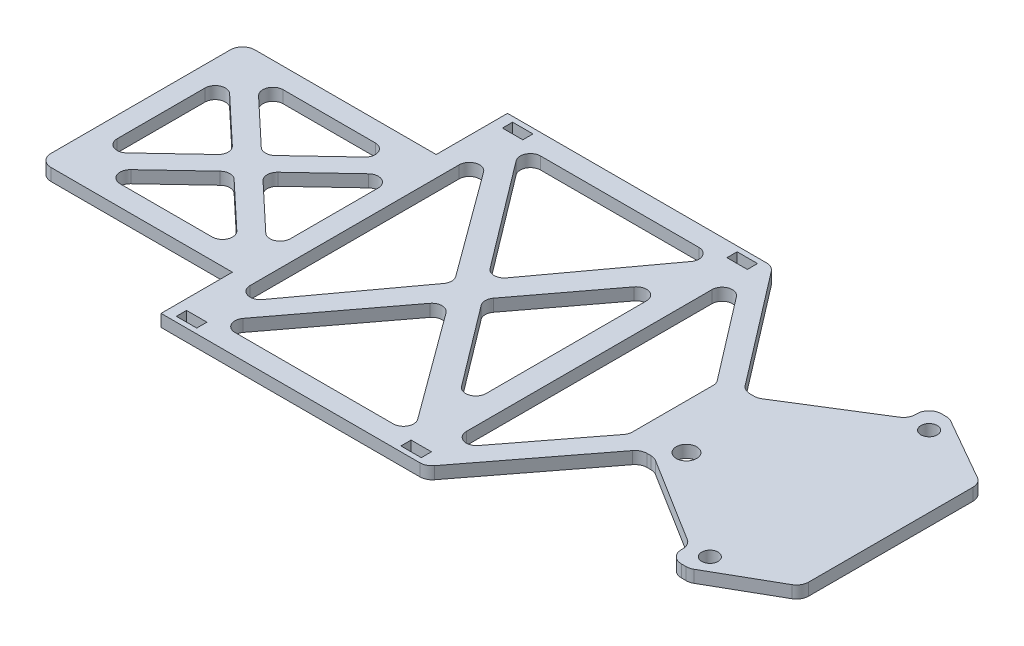
SolidWorks part; units mm, degrees
ref_plane "Front Plane" through (0, 0, 0) normal (0, 0, 1) x (1, 0, 0)
ref_plane "Top Plane" through (0, 0, 0) normal (0, 1, 0) x (1, 0, 0)
ref_plane "Right Plane" through (0, 0, 0) normal (1, 0, 0) x (0, 0, -1)
sketch "Sketch1" plane through (0, 0, 0) normal (0, 1, 0) x (1, 0, 0)
  line L0 (35, -25) -> (35, -35)
  line L1 (0, 0) -> (70, 0)
  line L2 (0, 0) -> (0, -25)
  line L3 (0, -25) -> (70, -25)
  line L4 (70, 0) -> (70, -25)
  line L5 (35, -35) -> (35, -85) construction
  line L6 (35, -85) -> (285, -85) construction
  line L7 (70, -170) -> (70, -145)
  line L8 (0, -145) -> (70, -145)
  line L9 (0, -170) -> (0, -145)
  line L10 (0, -170) -> (70, -170)
  line L11 (35, -145) -> (35, -135)
  line L12 (277.3319, -59.724) -> (274.2495, -59.724)
  line L13 (70, -170) -> (70, -145)
  line L14 (0, -170) -> (0, -145)
  line L15 (0, 0) -> (0, -25)
  line L16 (70, 0) -> (70, -25)
  line L17 (0, 0) -> (0, -25)
  line L18 (70, 0) -> (70, -25)
  line L19 (70, -170) -> (70, -145)
  line L20 (0, -170) -> (0, -145)
  line L21 (70, -170) -> (70, -145)
  line L22 (0, -170) -> (0, -145)
  line L23 (0, 0) -> (0, -25)
  line L24 (70, 0) -> (70, -25)
  line L25 (0, 0) -> (0, -25)
  line L26 (70, 0) -> (70, -25)
  line L27 (70, -170) -> (70, -145)
  line L28 (0, -170) -> (0, -145)
  line L29 (70, -170) -> (70, -145)
  line L30 (0, -170) -> (0, -145)
  line L31 (0, 0) -> (0, -25)
  line L32 (70, 0) -> (70, -25)
  line L33 (0, 0) -> (0, -25)
  line L34 (70, 0) -> (70, -25)
  line L35 (70, -170) -> (70, -145)
  line L36 (0, -170) -> (0, -145)
  line L37 (70, -170) -> (70, -145)
  line L38 (0, -170) -> (0, -145)
  line L39 (0, 0) -> (0, -25)
  line L40 (70, 0) -> (70, -25)
  line L41 (0, 0) -> (0, -25)
  line L42 (70, 0) -> (70, -25)
  line L43 (70, -170) -> (70, -145)
  line L44 (0, -170) -> (0, -145)
  line L45 (70, -170) -> (70, -145)
  line L46 (0, -170) -> (0, -145)
  line L47 (0, 0) -> (0, -25)
  line L48 (70, 0) -> (70, -25)
  line L49 (0, 0) -> (0, -25)
  line L50 (70, 0) -> (70, -25)
  line L51 (70, -170) -> (70, -145)
  line L52 (0, -170) -> (0, -145)
  line L53 (70, -170) -> (70, -145)
  line L54 (0, -170) -> (0, -145)
  line L55 (0, 0) -> (0, -25)
  line L56 (70, 0) -> (70, -25)
  line L57 (0, 0) -> (0, -25)
  line L58 (70, 0) -> (70, -25)
  line L59 (70, -170) -> (70, -145)
  line L60 (0, -170) -> (0, -145)
  line L61 (70, -170) -> (70, -145)
  line L62 (0, -170) -> (0, -145)
  line L63 (0, 0) -> (0, -25)
  line L64 (70, 0) -> (70, -25)
  line L65 (0, 0) -> (0, -25)
  line L66 (70, 0) -> (70, -25)
  line L67 (70, -170) -> (70, -145)
  line L68 (0, -170) -> (0, -145)
  line L69 (70, -170) -> (70, -145)
  line L70 (0, -170) -> (0, -145)
  line L71 (0, 0) -> (0, -25)
  line L72 (70, 0) -> (70, -25)
  line L73 (0, -85) -> (516.4371, -85) construction
  line L74 (368.0761, -41.2115) -> (368.0761, -128.7885)
  line L75 (323.0761, -31.2115) -> (277.3319, -59.724)
  line L76 (323.0761, -21.2115) -> (333.0761, -21.2115)
  line L77 (323.0761, -31.2115) -> (323.0761, -21.2115)
  line L78 (333.0761, -21.2115) -> (368.0761, -41.2115)
  line L79 (225, 0) -> (270.7934, -59.724)
  line L80 (270.7934, -59.724) -> (274.2495, -59.724)
  line L143 (0, -35) -> (95, -35)
  line L144 (95, -35) -> (95, 0)
  line L145 (95, 0) -> (225, 0)
  line L149 (0, -35) -> (0, -135)
  line L151 (270.7934, -110.276) -> (274.2495, -110.276)
  line L152 (225, -170) -> (270.7934, -110.276)
  line L153 (95, -170) -> (225, -170)
  line L154 (95, -135) -> (95, -170)
  line L155 (0, -135) -> (95, -135)
  line L159 (333.0761, -148.7885) -> (368.0761, -128.7885)
  line L164 (323.0761, -138.7885) -> (323.0761, -148.7885)
  line L165 (323.0761, -148.7885) -> (333.0761, -148.7885)
  line L166 (323.0761, -138.7885) -> (277.3319, -110.276)
  line L167 (277.3319, -110.276) -> (274.2495, -110.276)
  circle A1 centre (333.0761, -138.7885) radius 4
  circle A2 centre (333.0761, -31.2115) radius 4
  point P16 (0, 0)
  point P17 (0, 0)
  point P21 (0, 0)
  point P39 (368.0761, -85)
  point P44 (0, -85)
  dimension "D7" = 25.276
  dimension "D1" = 70
  dimension "D2" = 25
  dimension "D3" = 10
  dimension "D4" = 50
  dimension "D5" = 250
  dimension "D6" = 25
  dimension "D8" = 63.7885
  dimension "D9" = 43.7885
  dimension "D10" = 130
  dimension "D11" = 127.479
  dimension "D13" = 148.065
  dimension "D14" = 53.7885
  dimension "D17" = 53.7885
  dimension "D20" = 6.5385
extrude "Boss-Extrude1" add sketch "Sketch1" along normal blind 6 contours L12 L80 L79 L145 L144 L143 L149 L155 L154 L153 L152 L151 L167 L166 L164 L165 L159 L74 L78 L76 L77 L75 | A1 | A2
fillet "Fillet1" radius 6 16 edges at (270.7934, 3, 110.276) (0, 3, 35) (0, 3, 135) (333.0761, 3, 148.7885) (323.0761, 3, 148.7885) (225, 3, 170) (277.3319, 3, 110.276) (323.0761, 3, 138.7885) (225, 3, 0) (270.7934, 3, 59.724) (277.3319, 3, 59.724) (323.0761, 3, 31.2115) (323.0761, 3, 21.2115) (333.0761, 3, 21.2115) (368.0761, 3, 41.2115) (368.0761, 3, 128.7885)
sketch "Sketch2" plane through (0, 6, 0) normal (0, 1, 0) x (1, 0, 0)
  line L0 (285, -26.5175) -> (285, -151.0594) construction
  line L1 (368.0761, -88.7885) -> (285, -88.7885) construction
  line L2 (220.0663, -10) -> (220.0663, -160)
  line L3 (52.5, -91.8662) -> (17.2954, -125)
  line L4 (52.5, -91.8662) -> (87.7046, -125)
  line L5 (59.7954, -85) -> (95, -118.1338)
  line L6 (59.7954, -85) -> (52.5, -91.8662) construction
  line L7 (56.1477, -88.4331) -> (103.2003, -132.718) construction
  line L8 (95, -118.1338) -> (105, -118.1338) construction
  line L9 (100, -118.1338) -> (100, -135.6571) construction
  line L10 (52.5, -78.1338) -> (59.7954, -85) construction
  line L11 (100, -118.1338) -> (100, -34.3104) construction
  line L12 (87.7046, -45) -> (95, -51.8662) construction
  line L13 (56.1477, -81.5669) -> (103.2003, -36.5175) construction
  line L14 (208.7996, -30.7247) -> (208.7996, -139.2753)
  line L19 (105, -45) -> (105, -125)
  line L20 (261.0565, -63.4595) -> (261.0565, -106.5405)
  line L23 (105, -18.455) -> (153.7996, -85)
  line L24 (208.7996, -10) -> (160.7095, -75.5774)
  line L25 (111.2004, -10) -> (160.7095, -75.5774)
  line L26 (208.7996, -30.7247) -> (167.8233, -85)
  line L27 (167.8233, -85) -> (208.7996, -139.2753)
  line L29 (153.7996, -85) -> (105, -151.545)
  line L32 (160.7095, -94.4226) -> (111.2004, -160)
  line L34 (160.7095, -94.4226) -> (208.7996, -160)
  line L36 (332.4355, -137.637) -> (358.0761, -122.9852)
  line L37 (358.0761, -122.9852) -> (358.0761, -47.0148)
  line L38 (275.6151, -69.724) -> (273.7537, -69.724)
  line L42 (220.0663, -10) -> (105, -10)
  line L43 (105, -10) -> (105, -45)
  line L44 (105, -45) -> (10, -45)
  line L45 (10, -45) -> (10, -125)
  line L46 (10, -125) -> (105, -125)
  line L47 (105, -125) -> (105, -160)
  line L48 (105, -160) -> (220.0663, -160)
  line L49 (220.0663, -160) -> (261.0565, -106.5405)
  line L50 (273.7537, -100.276) -> (275.6151, -100.276)
  line L58 (208.7996, -10) -> (111.2004, -10)
  line L59 (105, -18.455) -> (105, -45)
  line L63 (105, -125) -> (105, -151.545)
  line L64 (111.2004, -160) -> (208.7996, -160)
  line L65 (220.0663, -160) -> (261.0565, -106.5405)
  line L76 (358.0761, -122.9852) -> (358.0761, -47.0148)
  line L77 (358.0761, -47.0148) -> (332.4355, -32.363)
  line L78 (284.0785, -102.6977) -> (325.5395, -128.5404)
  line L79 (284.0785, -102.6977) -> (325.5395, -128.5404)
  line L80 (358.0761, -47.0148) -> (332.4355, -32.363)
  line L81 (10, -45) -> (95, -45)
  line L82 (17.2954, -45) -> (87.7046, -45)
  line L84 (10, -45) -> (10, -125)
  line L85 (10, -51.8662) -> (10, -118.1338)
  line L86 (95, -51.8662) -> (95, -118.1338)
  line L87 (10, -125) -> (95, -125)
  line L88 (17.2954, -125) -> (87.7046, -125)
  line L90 (325.5395, -41.4596) -> (284.0785, -67.3023)
  line L91 (10, -51.8662) -> (45.2046, -85)
  line L92 (87.7046, -45) -> (52.5, -78.1338)
  line L93 (17.2954, -45) -> (52.5, -78.1338)
  line L94 (95, -51.8662) -> (59.7954, -85)
  line L95 (325.5395, -41.4596) -> (284.0785, -67.3023)
  line L96 (261.0565, -63.4595) -> (220.0663, -10)
  line L97 (261.0565, -63.4595) -> (220.0663, -10)
  line L100 (95, -45) -> (95, -125) construction
  line L102 (45.2046, -85) -> (10, -118.1338)
  circle A2 centre (285, -36.5175) radius 4
  circle A3 centre (285, -141.0594) radius 4
  arc A21 (325.5395, -41.4596) -> (332.4355, -32.363) centre (317.0761, -27.8813) ccw
  arc A22 (284.0785, -102.6977) -> (275.6151, -100.276) centre (275.6151, -116.276) ccw
  arc A23 (284.0785, -102.6977) -> (275.6151, -100.276) centre (275.6151, -116.276) ccw
  arc A26 (273.7537, -100.276) -> (261.0565, -106.5405) centre (273.7537, -116.276) ccw
  arc A27 (332.4355, -137.637) -> (325.5395, -128.5404) centre (317.0761, -142.1187) ccw
  arc A28 (332.4355, -137.637) -> (325.5395, -128.5404) centre (317.0761, -142.1187) ccw
  arc A31 (325.5395, -41.4596) -> (332.4355, -32.363) centre (317.0761, -27.8813) ccw
  arc A32 (275.6151, -69.724) -> (284.0785, -67.3023) centre (275.6151, -53.724) ccw
  arc A33 (275.6151, -69.724) -> (284.0785, -67.3023) centre (275.6151, -53.724) ccw
  arc A34 (261.0565, -63.4595) -> (273.7537, -69.724) centre (273.7537, -53.724) ccw
  dimension "D1" = 10
  dimension "D2" = 8
  dimension "D3" = 10
  dimension "D4" = 10
  dimension "D5" = 10
  dimension "D6" = 10
  dimension "D7" = 10
extrude "Cut-Extrude1" cut sketch "Sketch2" against normal blind 6 contours L26 L27 L14 | L20 L97 L2 L65
fillet "Fillet3" radius 5 28 edges at (208.7996, 3, 160) (160.7095, 3, 94.4226) (111.2004, 3, 160) (167.8233, 3, 85) (160.7095, 3, 75.5774) (153.7996, 3, 85) (105, 3, 151.545) (105, 3, 18.455) (111.2004, 3, 10) (208.7996, 3, 10) (17.2954, 3, 45) (10, 3, 51.8662) (45.2046, 3, 85) (52.5, 3, 91.8662) (87.7046, 3, 125) (17.2954, 3, 125) (10, 3, 118.1338) (52.5, 3, 78.1338) (59.7954, 3, 85) (95, 3, 118.1338) (87.7046, 3, 45) (95, 3, 51.8662) (261.0565, 3, 106.5405) (261.0565, 3, 63.4595) (220.0663, 3, 10) (220.0663, 3, 160) (208.7996, 3, 139.2753) (208.7996, 3, 30.7247)
sketch "Sketch3" plane through (0, 6, 0) normal (0, 1, 0) x (1, 0, 0)
  line L1 (368.0761, -44.6935) -> (368.0761, -125.3065) construction
  line L2 (283.0761, -100.276) -> (283.0761, -110.276) construction
  line L3 (275.6151, -110.276) -> (273.7537, -110.276) construction
  circle A0 centre (283.0761, -100.276) radius 5.01
  dimension "D2" = 10
  dimension "D1" = 85
extrude "Cut-Extrude2" cut sketch "Sketch3" against normal blind 10 contours A0
sketch "Sketch4" plane through (0, 6, 0) normal (0, 1, 0) x (1, 0, 0)
  line L0 (160.0864, -10) -> (160.0864, 0) construction
  line L1 (198.9326, -10) -> (121.2402, -10) construction
  line L2 (95, 0) -> (222.0398, 0) construction
  line L3 (160.0864, 0) -> (160.0864, -5) construction
  line L4 (160.0864, -5) -> (62.5044, -5) construction
  line L5 (95, -35) -> (95, 0) construction
  line L6 (110, -2.5) -> (100, -2.5)
  line L7 (110, -2.5) -> (110, -7.5)
  line L8 (110, -7.5) -> (100, -7.5)
  line L9 (100, -2.5) -> (100, -7.5)
  line L10 (110, -2.5) -> (100, -7.5) construction
  line L11 (110, -7.5) -> (100, -2.5) construction
  line L12 (220.1728, -2.5) -> (220.1728, -7.5)
  line L13 (210.1728, -7.5) -> (220.1728, -7.5)
  line L14 (210.1728, -2.5) -> (210.1728, -7.5)
  line L15 (210.1728, -2.5) -> (220.1728, -2.5)
  line L16 (0, -85) -> (386.1789, -85) construction
  line L17 (0, -41) -> (0, -129) construction
  line L18 (110, -162.5) -> (100, -167.5) construction
  line L19 (110, -167.5) -> (100, -162.5) construction
  line L20 (160.0864, -165) -> (62.5044, -165) construction
  line L21 (160.0864, -170) -> (160.0864, -165) construction
  line L22 (160.0864, -160) -> (160.0864, -170) construction
  line L23 (210.1728, -167.5) -> (220.1728, -167.5)
  line L24 (210.1728, -167.5) -> (210.1728, -162.5)
  line L25 (210.1728, -162.5) -> (220.1728, -162.5)
  line L26 (220.1728, -167.5) -> (220.1728, -162.5)
  line L27 (100, -167.5) -> (100, -162.5)
  line L28 (110, -162.5) -> (100, -162.5)
  line L29 (110, -167.5) -> (110, -162.5)
  line L30 (110, -167.5) -> (100, -167.5)
  point P6 (105, -5)
  point P36 (105, -165)
  dimension "D1" = 10
  dimension "D2" = 5
  dimension "D3" = 5
extrude "Cut-Extrude3" cut sketch "Sketch4" against normal blind 10
